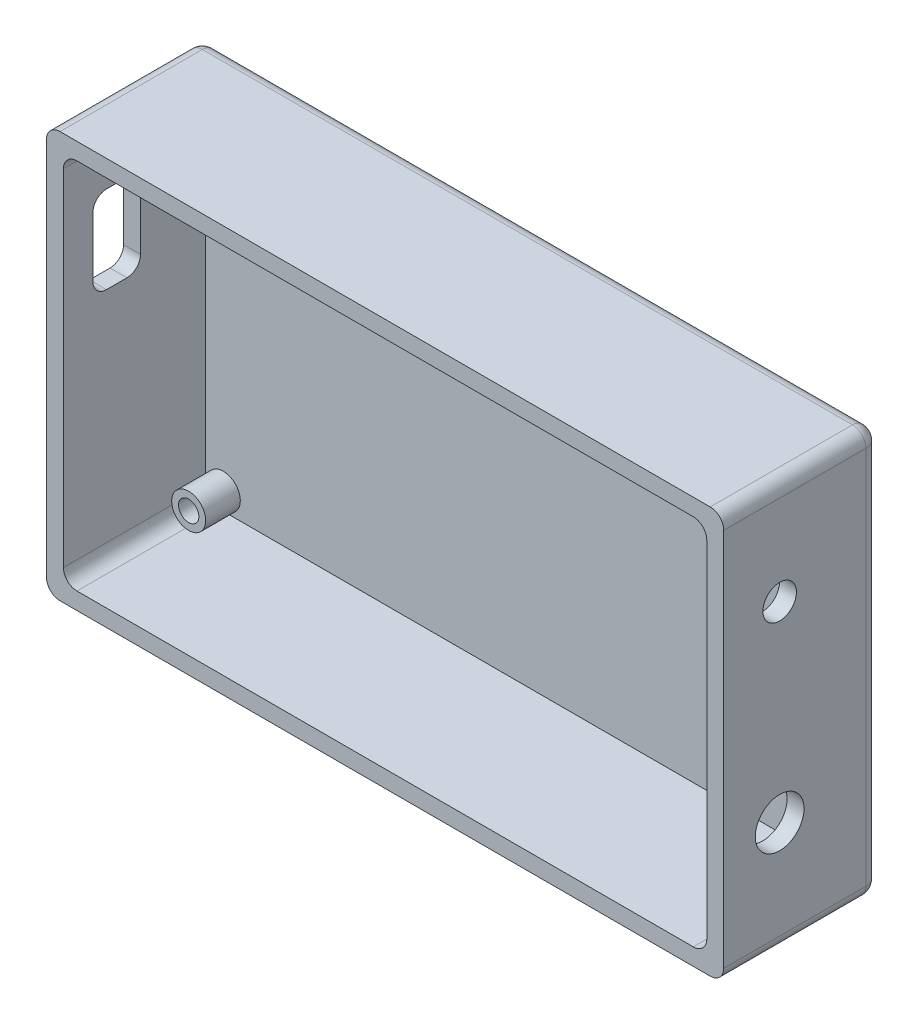
SolidWorks part; units mm, degrees
ref_plane "Front Plane" through (0, 0, 0) normal (0, 0, 1) x (1, 0, 0)
ref_plane "Top Plane" through (0, 0, 0) normal (0, 1, 0) x (1, 0, 0)
ref_plane "Right Plane" through (0, 0, 0) normal (1, 0, 0) x (0, 0, -1)
sketch "Sketch1" plane through (0, 0, 0) normal (0, 0, 1) x (1, 0, 0)
  line L1 (-50, -30) -> (50, -30)
  line L2 (-50, -30) -> (-50, 30)
  line L3 (-50, 30) -> (50, 30)
  line L4 (50, -30) -> (50, 30)
  line L5 (-50, -30) -> (50, 30) construction
  line L6 (-50, 30) -> (50, -30) construction
  point P0 (0, 0)
  dimension "D1" = 100
  dimension "D2" = 60
extrude "Boss-Extrude1" add sketch "Sketch1" along normal blind 23
sketch "Sketch2" plane through (0, 0, 23) normal (0, 0, 1) x (1, 0, 0)
  line L14 (-47.5, 27.5) -> (-47.5, -27.5)
  line L15 (-47.5, -27.5) -> (47.5, -27.5)
  line L16 (47.5, -27.5) -> (47.5, 27.5)
  line L17 (47.5, 27.5) -> (-47.5, 27.5)
  line L18 (-47.5, 27.5) -> (-47.5, -27.5)
  line L19 (-47.5, -27.5) -> (47.5, -27.5)
  line L20 (47.5, -27.5) -> (47.5, 27.5)
  line L21 (47.5, 27.5) -> (-47.5, 27.5)
  dimension "D1" = 2.5
extrude "Cut-Extrude1" cut sketch "Sketch2" against normal blind 21
sketch "Sketch3" plane through (0, 0, 2) normal (0, 0, 1) x (1, 0, 0)
  line L1 (50, 30) -> (-50, 30) construction
  line L2 (-50, 30) -> (-50, -30) construction
  line L7 (-47.5, 27.5) -> (-47.5, -27.5) construction
  circle A0 centre (-44.89, 24.89) radius 2.51
  circle A1 centre (-44.89, 24.89) radius 1.5
  point P4 (-44.89, 22.38)
  point P5 (-42.38, 24.89)
  point P8 (-44.89, 27.4344)
  point P11 (-47.4, 24.89)
  dimension "D1" = 7.62
  dimension "D3" = 3
  dimension "D2" = 7.62
  dimension "D4" = 0.1
extrude "Boss-Extrude6" add sketch "Sketch3" along normal blind 5.112
mirror "Mirror1" about plane through (0, 0, 0) normal (0, 1, 0) of "Boss-Extrude6"
mirror "Mirror2" about plane through (0, 0, 0) normal (1, 0, 0) of "Mirror1", "Boss-Extrude6"
fillet "Fillet1" radius 2 12 edges at (0, 30, 0) (-50, 30, 11.5) (-50, 0, 0) (-50, -30, 11.5) (0, -30, 0) (50, 0, 0) (50, 30, 11.5) (50, -30, 11.5) (47.5, -27.5, 12.5) (47.5, 27.5, 12.5) (-47.5, 27.5, 12.5) (-47.5, -27.5, 12.5)
sketch "Sketch4" plane through (-50, 0, 0) normal (-1, 0, 0) x (0, 0, 1)
  line L1 (18.6397, 19.7233) -> (11.612, 19.7233)
  line L2 (18.6397, 19.7233) -> (18.6397, 6.86)
  line L3 (18.6397, 6.86) -> (11.612, 6.86)
  line L4 (11.612, 19.7233) -> (11.612, 6.86)
extrude "Cut-Extrude2" cut sketch "Sketch4" against normal up to next
fillet "Fillet2" radius 2 4 edges at (-48.75, 19.7233, 11.612) (-48.75, 6.86, 11.612) (-48.75, 6.86, 18.6397) (-48.75, 19.7233, 18.6397)
sketch "Sketch5" plane through (50, 0, 0) normal (1, 0, 0) x (0, 0, -1)
  line L0 (-2, -30) -> (-23, -30) construction
  line L1 (-23, -25.5) -> (-23, 25.5) construction
  line L3 (-23, 30) -> (-2, 30) construction
  circle A0 centre (-14.74, -13.49) radius 3.6
  circle A1 centre (-14.74, 14.76) radius 2.475
  dimension "D1" = 16.51
  dimension "D3" = 7.2
  dimension "D6" = 4.95
  dimension "D2" = 8.26
  dimension "D4" = 8.26
  dimension "D5" = 15.24
extrude "Cut-Extrude3" cut sketch "Sketch5" against normal up to next
